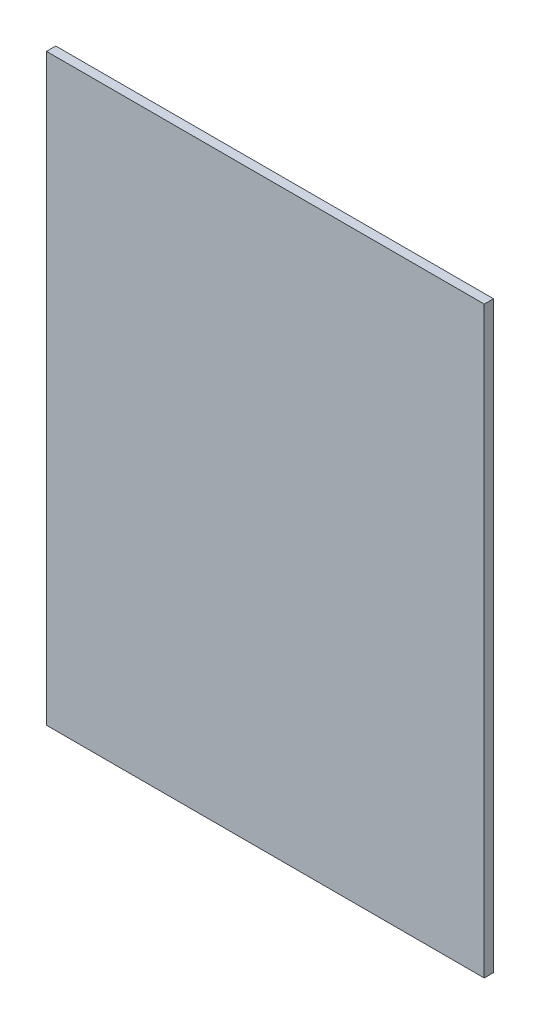
SolidWorks part; units mm, degrees
ref_plane "Front Plane" through (0, 0, 0) normal (0, 0, 1) x (1, 0, 0)
ref_plane "Top Plane" through (0, 0, 0) normal (0, 1, 0) x (1, 0, 0)
ref_plane "Right Plane" through (0, 0, 0) normal (1, 0, 0) x (0, 0, -1)
sketch "Sketch1" plane through (0, 0, 0) normal (0, 0, 1) x (1, 0, 0)
  line L1 (-37.0676, 383.1744) -> (262.9324, 383.1744)
  line L2 (-37.0676, 383.1744) -> (-37.0676, -16.8256)
  line L3 (-37.0676, -16.8256) -> (262.9324, -16.8256)
  line L4 (262.9324, 383.1744) -> (262.9324, -16.8256)
  dimension "D1" = 400
  dimension "D2" = 300
extrude "Boss-Extrude1" add sketch "Sketch1" along normal blind 6.35
